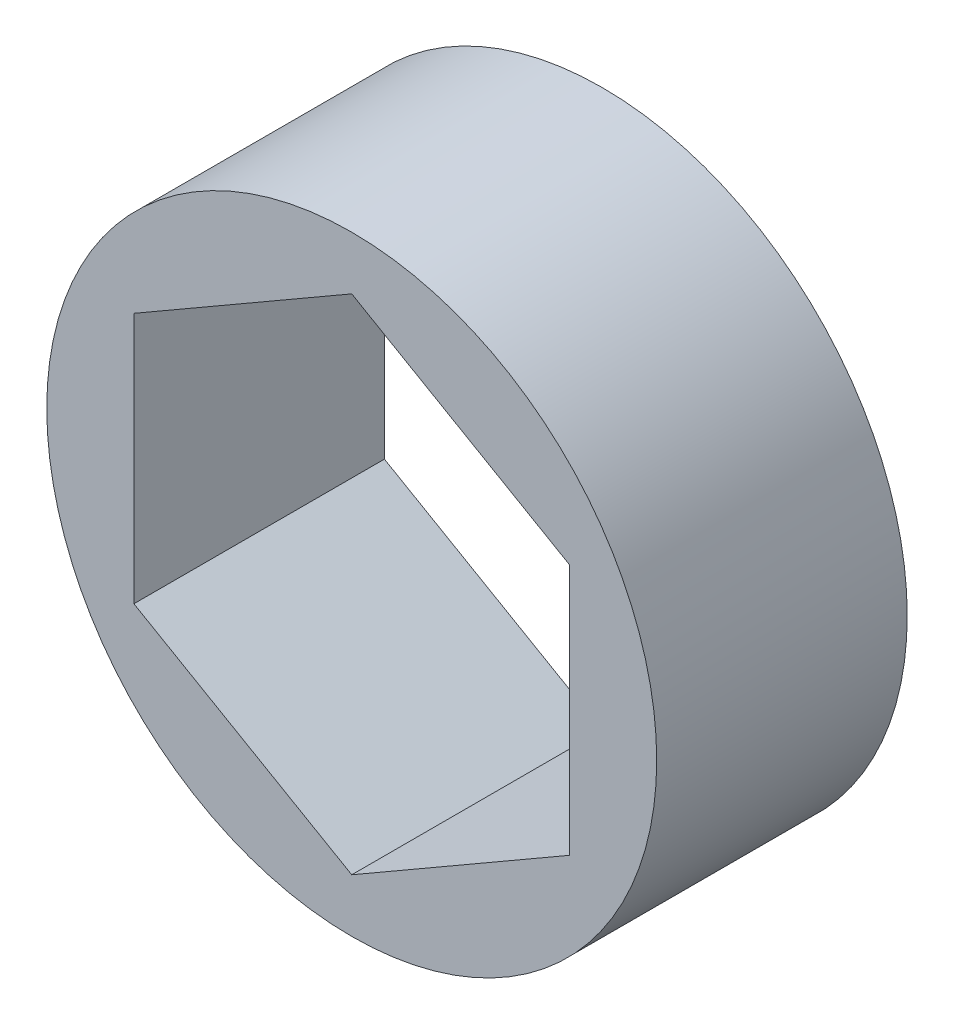
SolidWorks part; units mm, degrees
material "PET"
ref_plane "Front Plane" through (0, 0, 0) normal (0, 0, 1) x (1, 0, 0)
ref_plane "Top Plane" through (0, 0, 0) normal (0, 1, 0) x (1, 0, 0)
ref_plane "Right Plane" through (0, 0, 0) normal (1, 0, 0) x (0, 0, -1)
sketch "Sketch1" plane through (0, 0, 0) normal (0, 0, 1) x (1, 0, 0)
  line L1 (0, 7.3323) -> (-6.35, 3.6662)
  line L2 (-6.35, 3.6662) -> (-6.35, -3.6662)
  line L3 (-6.35, -3.6662) -> (0, -7.3323)
  line L4 (0, -7.3323) -> (6.35, -3.6662)
  line L5 (6.35, -3.6662) -> (6.35, 3.6662)
  line L6 (6.35, 3.6662) -> (0, 7.3323)
  circle A0 centre (0, 0) radius 6.35 construction
  circle A1 centre (0, 0) radius 8.89
  dimension "D1" = 12.7
  dimension "D2" = 17.78
extrude "Boss-Extrude1" add sketch "Sketch1" along normal mid plane 7.3025
